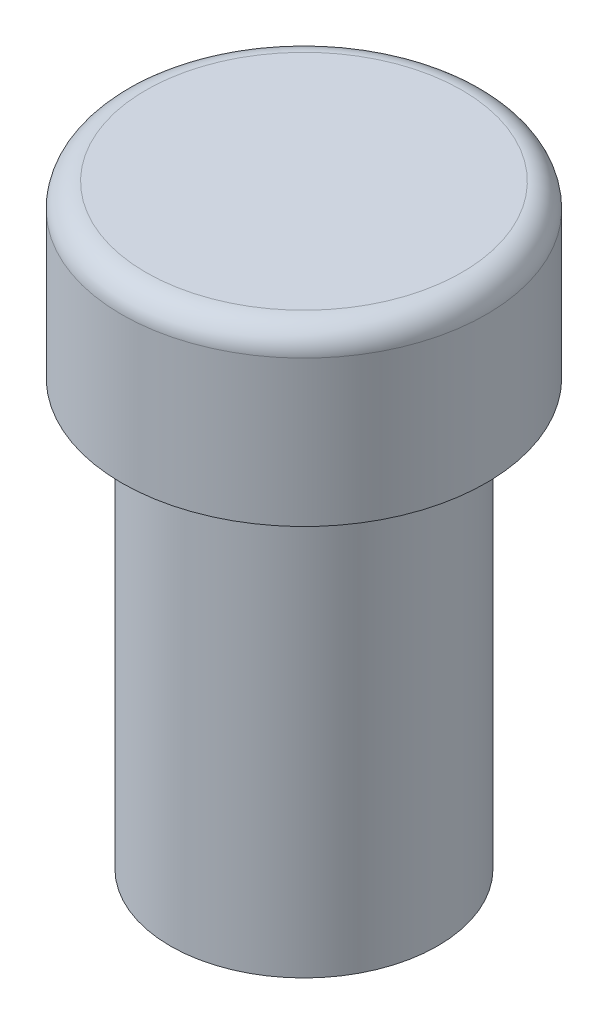
SolidWorks part; units mm, degrees
ref_plane "Спереди" through (0, 0, 0) normal (0, 0, 1) x (1, 0, 0)
ref_plane "Сверху" through (0, 0, 0) normal (0, 1, 0) x (1, 0, 0)
ref_plane "Справа" through (0, 0, 0) normal (1, 0, 0) x (0, 0, -1)
sketch "Эскиз1" plane through (0, 0, 0) normal (0, 1, 0) x (1, 0, 0)
  circle A0 centre (0, 0) radius 11
extrude "Вытянуть1" add sketch "Эскиз1" along normal blind 35
sketch "Эскиз2" plane through (0, 35, 0) normal (0, 1, 0) x (1, 0, 0)
  circle A0 centre (0, 0) radius 15
extrude "Вытянуть2" add sketch "Эскиз2" along normal blind 14
fillet "Скругление1" radius 2 1 edges at (0, 49, 15)
